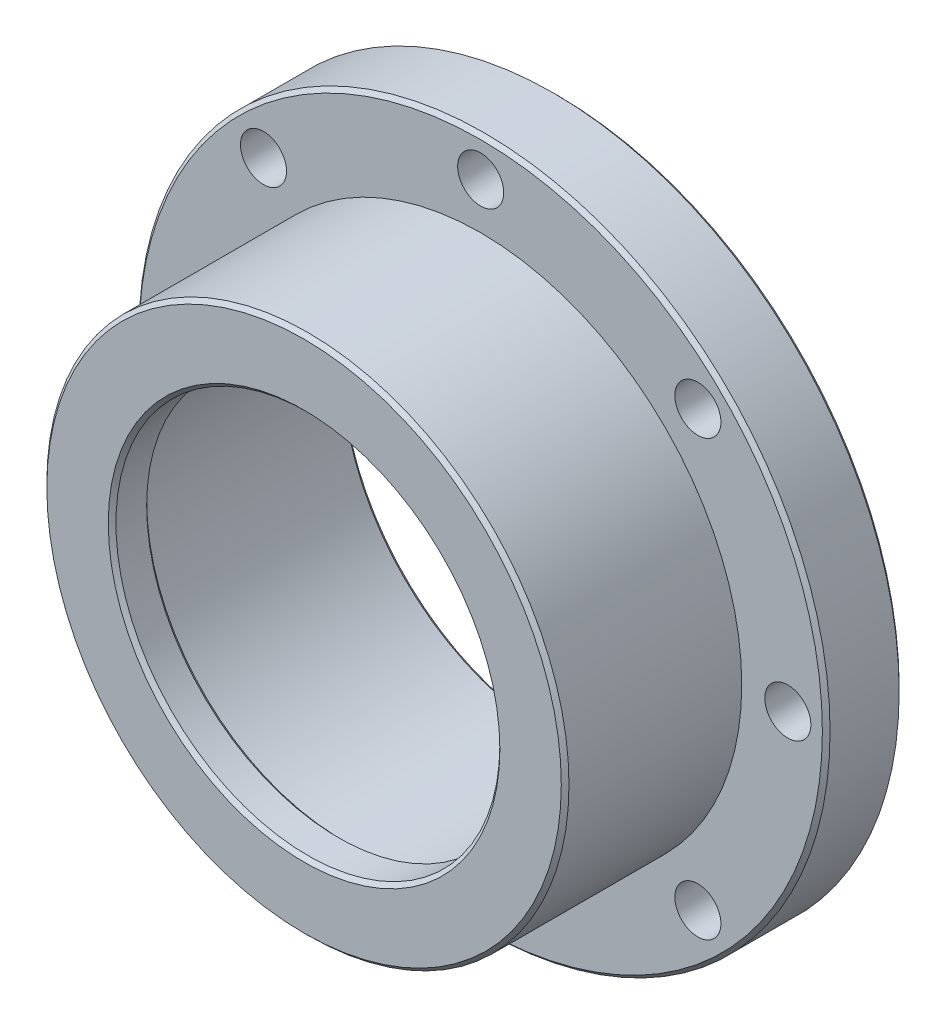
SolidWorks part; units mm, degrees
ref_plane "前视基准面" through (0, 0, 0) normal (0, 0, 1) x (1, 0, 0)
ref_plane "上视基准面" through (0, 0, 0) normal (0, 1, 0) x (1, 0, 0)
ref_plane "右视基准面" through (0, 0, 0) normal (1, 0, 0) x (0, 0, -1)
sketch "草图1" plane through (0, 0, 0) normal (0, 0, 1) x (1, 0, 0)
  circle A0 centre (0, 0) radius 45
  dimension "D1" = 90
extrude "拉伸1" add sketch "草图1" along normal blind 10
sketch "草图2" plane through (0, 0, 10) normal (0, 0, 1) x (1, 0, 0)
  circle A0 centre (0, 0) radius 34
  dimension "D1" = 68
extrude "拉伸2" add sketch "草图2" along normal blind 23
sketch "草图4" plane through (0, 0, 33) normal (0, 0, 1) x (1, 0, 0)
  circle A0 centre (0, 0) radius 25
  dimension "D1" = 50
extrude "切除-拉伸1" cut sketch "草图4" against normal blind 70
sketch "草图5" plane through (0, 0, 0) normal (0, 0, -1) x (-1, 0, 0)
  circle A0 centre (0, 0) radius 27.5
  dimension "D1" = 55
extrude "切除-拉伸2" cut sketch "草图5" against normal blind 28
sketch "草图6" plane through (0, 0, 10) normal (0, 0, 1) x (1, 0, 0)
  circle A0 centre (28.2843, 28.2843) radius 3
  circle A1 centre (40, 0) radius 3
  circle A2 centre (28.2843, -28.2843) radius 3
  circle A3 centre (0, -40) radius 3
  circle A4 centre (-28.2843, -28.2843) radius 3
  circle A5 centre (0, 40) radius 3
  circle A6 centre (-40, 0) radius 3
  circle A7 centre (-28.2843, 28.2843) radius 3
extrude "切除-拉伸3" cut sketch "草图6" against normal blind 25
chamfer "倒角1" distance 0.5 angle 45 6 edges at (-25, 0, 28) (-27.5, 0, 0) (45, 0, 0) (45, 0, 10) (25, 0, 33) (34, 0, 33)
